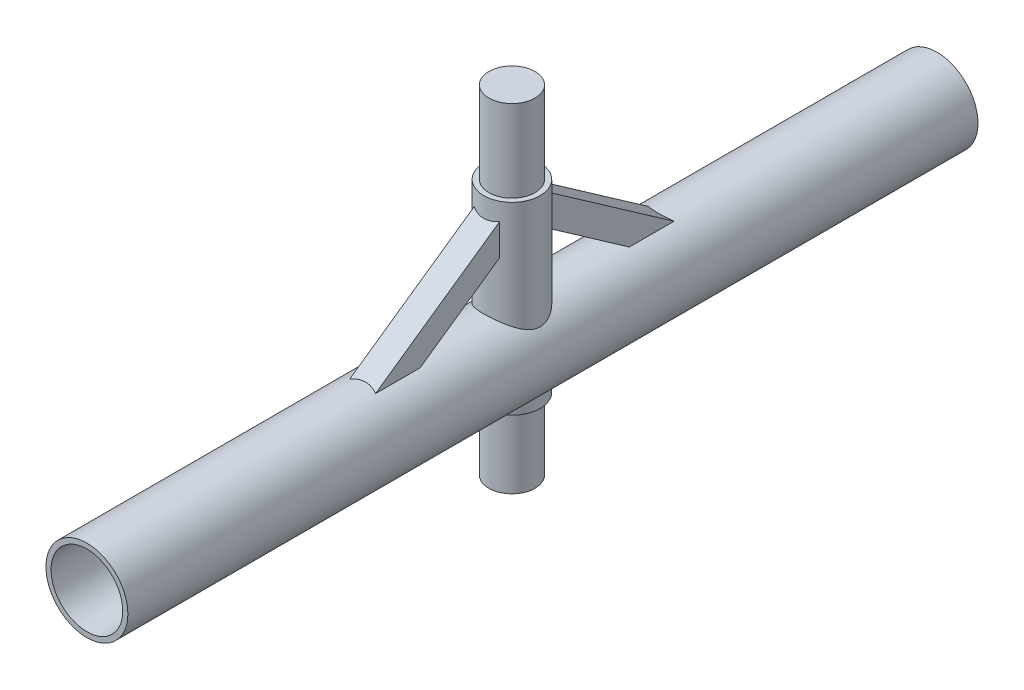
SolidWorks part; units mm, degrees
ref_plane "Front Plane" through (0, 0, 0) normal (0, 0, 1) x (1, 0, 0)
ref_plane "Top Plane" through (0, 0, 0) normal (0, 1, 0) x (1, 0, 0)
ref_plane "Right Plane" through (0, 0, 0) normal (1, 0, 0) x (0, 0, -1)
sketch "Sketch1" plane through (0, 0, 0) normal (0, 0, 1) x (1, 0, 0)
  circle A0 centre (0, 0) radius 40
  dimension "D1" = 80
extrude "Extrude-Thin1" add sketch "Sketch1" along normal mid plane 830 thin thin type one direction reverse wall 5
sketch "Sketch2" plane through (0, 0, 0) normal (0, 1, 0) x (1, 0, 0)
  circle A0 centre (0, 0) radius 22.5
  dimension "D1" = 45
extrude "Extrude-Thin2" add sketch "Sketch2" along normal blind 140 and the other way blind 40 thin
sketch "Sketch3" plane through (0, 140, 0) normal (0, 1, 0) x (1, 0, 0)
  circle A0 centre (0, 0) radius 22.5 construction
  circle A1 centre (0, 0) radius 22.5
extrude "Boss-Extrude1" add sketch "Sketch3" along normal blind 80 and the other way offset from surface (250 mm away) 70 other way up to face at (0, -40, 0)
sketch "Sketch4" plane through (0, 0, 0) normal (1, 0, 0) x (0, 0, -1)
  line L0 (0, 140) -> (-200, 0)
  dimension "D1" = 140
  dimension "D2" = 200
extrude "Extrude-Thin3" add sketch "Sketch4" along normal mid plane 25 separate body thin thin type one direction reverse wall 25
mirror "Mirror1" about plane through (0, 0, 0) normal (0, 0, 1) of bodies 104
sketch "Sketch5" plane through (0, 0, 415) normal (0, 0, 1) x (1, 0, 0)
  circle A0 centre (0, 0) radius 35 construction
  circle A1 centre (0, 0) radius 35
extrude "Cut-Extrude1" cut sketch "Sketch5" against normal through all
